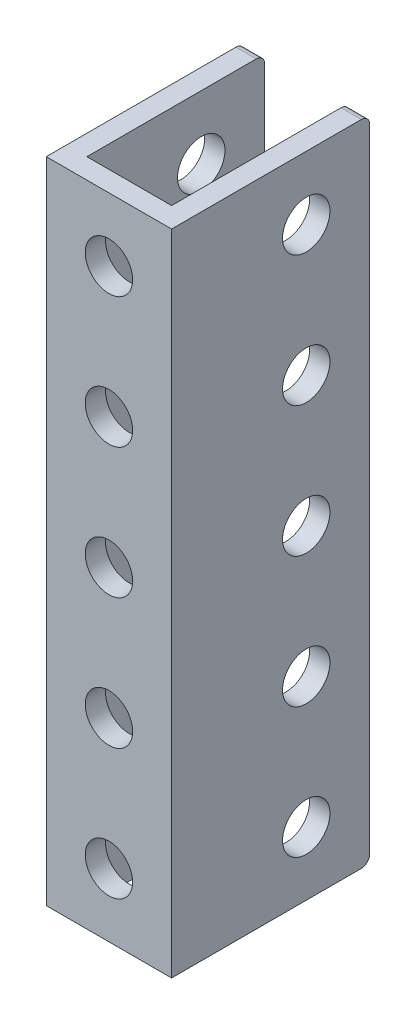
SolidWorks part; units mm, degrees
ref_plane "Front Plane" through (0, 0, 0) normal (0, 0, 1) x (1, 0, 0)
ref_plane "Top Plane" through (0, 0, 0) normal (0, 1, 0) x (1, 0, 0)
ref_plane "Right Plane" through (0, 0, 0) normal (1, 0, 0) x (0, 0, -1)
ref_plane "Plane1" through (-4.699, 0, 0) normal (-1, 0, 0) x (0, -1, 0)
sketch "Sketch1" plane through (-4.699, 0, 0) normal (-1, 0, 0) x (0, -1, 0)
  line L0 (-48.641, -13.335) -> (0, -13.335)
  line L1 (0, -13.335) -> (0, 1.524)
  line L2 (0, 1.524) -> (-48.641, 1.524)
  line L3 (-48.641, 1.524) -> (-48.641, -13.335)
extrude "Boss-Extrude1" add sketch "Sketch1" against normal blind 9.398
sketch "Sketch2" plane through (0, 0, 0) normal (0, -1, 0) x (1, 0, 0)
  line L0 (-3.175, -13.335) -> (3.175, -13.335)
  line L1 (3.175, -13.335) -> (3.175, 0)
  line L2 (3.175, 0) -> (-3.175, 0)
  line L3 (-3.175, 0) -> (-3.175, -13.335)
extrude "Cut-Extrude1" cut sketch "Sketch2" against normal through all
hole_wizard "#5 Clearance Hole1" positions "Sketch4" profile "Sketch3" hole size "#5" standard "ANSI Inch"
sketch "Sketch4" plane through (4.699, 0, 0) normal (1, 0, 0) x (0, 0, -1)
  point P0 (8.5725, 34.0995)
  point P1 (8.5725, 43.8785)
  point P2 (8.5725, 24.3205)
  point P3 (8.5725, 14.5415)
  point P4 (8.5725, 4.7625)
sketch "Sketch3" plane through (4.699, 34.0995, -8.5725) normal (0, 1, 0) x (0, 0, -1)
  line L0 (0, 0) -> (0, 1.524)
  line L1 (0, 1.524) -> (1.778, 1.524)
  line L2 (1.778, 1.524) -> (1.778, 0)
  line L5 (1.778, 0) -> (0, 0)
  line L11 (0, -6.35) -> (0, 107.95) construction
  dimension "Thru Hole Dia." = 3.556
  dimension "Thru Hole Depth" = 1.524
hole_wizard "#5 Clearance Hole2" positions "Sketch6" profile "Sketch5" hole size "#5" standard "ANSI Inch"
sketch "Sketch6" plane through (0, 0, 1.524) normal (0, 0, 1) x (1, 0, 0)
  point P0 (0, 34.0995)
  point P1 (0, 43.8785)
  point P2 (0, 24.3205)
  point P3 (0, 14.5415)
  point P4 (0, 4.7625)
sketch "Sketch5" plane through (0, 34.0995, 1.524) normal (1, 0, 0) x (0, -1, 0)
  line L0 (0, 0) -> (0, 14.859)
  line L1 (0, 14.859) -> (1.778, 14.859)
  line L2 (1.778, 14.859) -> (1.778, 0)
  line L5 (1.778, 0) -> (0, 0)
  line L11 (0, -6.35) -> (0, 107.95) construction
  dimension "Thru Hole Dia." = 3.556
  dimension "Thru Hole Depth" = 14.859
hole_wizard "#5 Clearance Hole3" positions "Sketch8" profile "Sketch7" hole size "#5" standard "ANSI Inch"
sketch "Sketch8" plane through (-3.175, 0, 0) normal (1, 0, 0) x (0, 0, -1)
  point P0 (8.5725, 34.0995)
  point P1 (8.5725, 43.8785)
  point P2 (8.5725, 24.3205)
  point P3 (8.5725, 14.5415)
  point P4 (8.5725, 4.7625)
sketch "Sketch7" plane through (-3.175, 34.0995, -8.5725) normal (0, 1, 0) x (0, 0, -1)
  line L0 (0, 0) -> (0, 1.524)
  line L1 (0, 1.524) -> (1.778, 1.524)
  line L2 (1.778, 1.524) -> (1.778, 0)
  line L5 (1.778, 0) -> (0, 0)
  line L11 (0, -6.35) -> (0, 107.95) construction
  dimension "Thru Hole Dia." = 3.556
  dimension "Thru Hole Depth" = 1.524
fillet "Fillet1" radius 0.635 4 edges at (3.937, 0, -13.335) (3.937, 48.641, -13.335) (-3.937, 48.641, -13.335) (-3.937, 0, -13.335)
